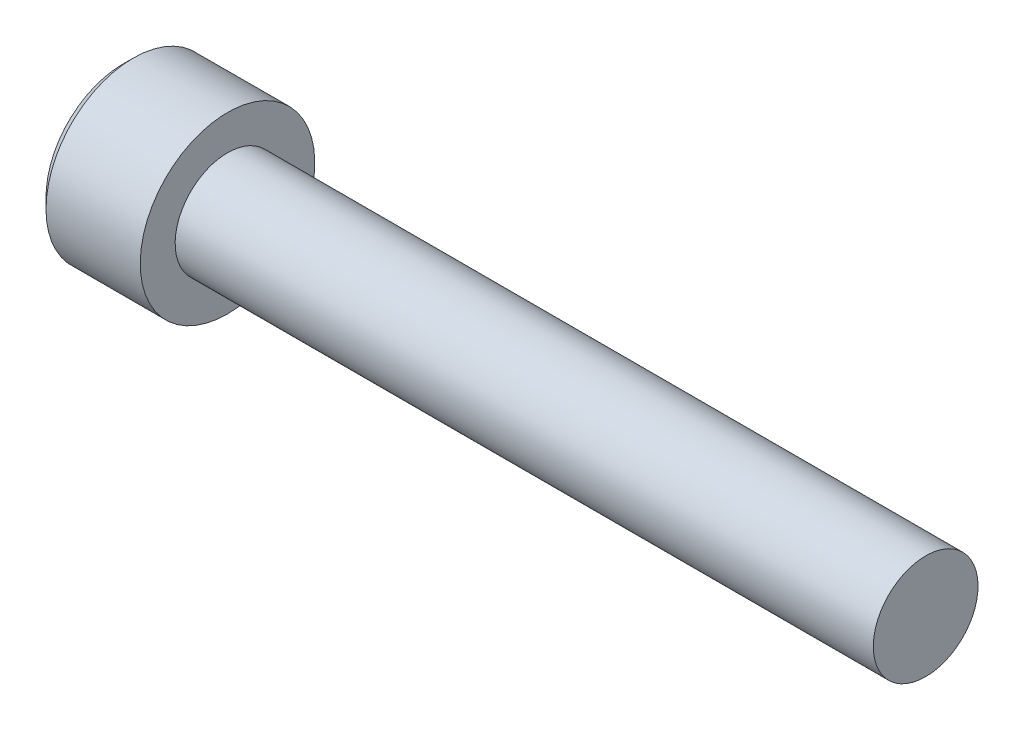
SolidWorks part; units mm, degrees
material "SCM435"
ref_plane "Front Plane" through (0, 0, 0) normal (0, 0, 1) x (1, 0, 0)
ref_plane "Top Plane" through (0, 0, 0) normal (0, 1, 0) x (1, 0, 0)
ref_plane "Right Plane" through (0, 0, 0) normal (1, 0, 0) x (0, 0, -1)
sketch "Sketch1" plane through (0, 0, 0) normal (0, 0, 1) x (1, 0, 0)
  line L0 (-6, 0) -> (40, 0) construction
  line L1 (0, 3) -> (40, 3)
  line L3 (-6, 0) -> (40, 0)
  line L4 (40, 3) -> (40, 0)
  line L6 (0, 3) -> (0, 5)
  line L7 (0, 5) -> (-6, 5)
  line L8 (-6, 0) -> (-6, 5)
  dimension "L" = 40
  dimension "M" = 6
  dimension "E" = 6
  dimension "A" = 10
revolve "Revolve1" add sketch "Sketch1" about L0
cosmetic thread "Thread1" parameters "L_s"=24, "ATD"=4.917
sketch "Sketch2" plane through (0, 0, 0) normal (0, 0, 1) x (1, 0, 0)
  line L0 (-6, 2.5) -> (-3, 2.5)
  line L1 (-6, 0) -> (-6, 5) construction
  line L2 (-3, 2.5) -> (-1.4978, 0)
  line L3 (-6, 0) -> (40, 0) construction
  line L4 (-1.4978, 0) -> (-6, 0) construction
  line L5 (-6, 0) -> (-6, 2.5)
  line L6 (-1.4978, 0) -> (-6, 0)
  dimension "FIX_2" = 59
  dimension "MSM_1" = 3
revolve "Cut-Revolve1" cut sketch "Sketch2" about L4
sketch "Sketch3" plane through (-6, 0, 0) normal (-1, 0, 0) x (0, 0, 1)
  line L0 (0, -3.025) -> (0, 3.025) construction
  line L1 (2.5, 1.4434) -> (0, 2.8868)
  line L2 (0, 2.8868) -> (-2.5, 1.4434)
  line L3 (-2.5, 1.4434) -> (-2.5, -1.4434)
  line L4 (-2.5, -1.4434) -> (0, -2.8868)
  line L5 (0, -2.8868) -> (2.5, -1.4434)
  line L6 (2.5, -1.4434) -> (2.5, 1.4434)
  circle A0 centre (0, 0) radius 2.5 construction
extrude "Cut-Extrude1" cut sketch "Sketch3" against normal blind 3
chamfer "Chamfer1" distance 0.6 1 edges at (-6, -5, 0)
